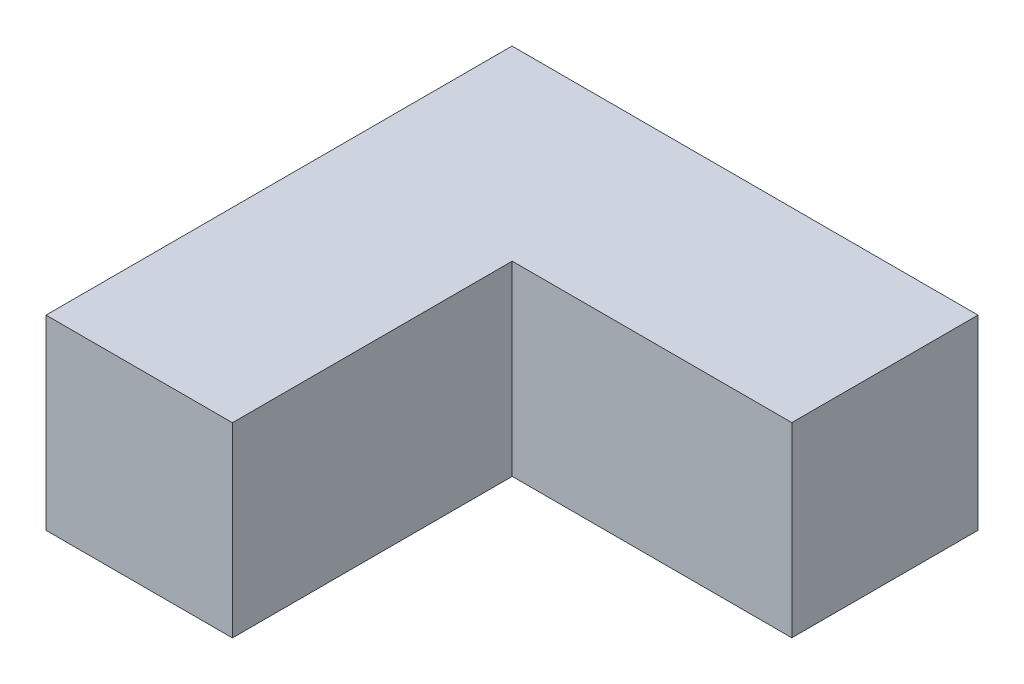
SolidWorks part; units mm, degrees
ref_plane "Plan de face" through (0, 0, 0) normal (0, 0, 1) x (1, 0, 0)
ref_plane "Plan de dessus" through (0, 0, 0) normal (0, 1, 0) x (1, 0, 0)
ref_plane "Plan de droite" through (0, 0, 0) normal (1, 0, 0) x (0, 0, -1)
sketch "Esquisse1" plane through (0, 0, 0) normal (1, 0, 0) x (0, 0, -1)
  line L1 (-2.4552, 0.3209) -> (2.5448, 0.3209)
  line L2 (-2.4552, 0.3209) -> (-2.4552, -1.6791)
  line L3 (-2.4552, -1.6791) -> (2.5448, -1.6791)
  line L4 (2.5448, 0.3209) -> (2.5448, -1.6791)
  dimension "D1" = 5
  dimension "D2" = 2
extrude "Boss.-Extru.1" add sketch "Esquisse1" along normal blind 2
sketch "Esquisse2" plane through (2, 0, 0) normal (1, 0, 0) x (0, 0, -1)
  line L0 (-2.4552, -1.6791) -> (2.5448, -1.6791) construction
  line L1 (2.5448, 0.3209) -> (0.5471, 0.3209)
  line L2 (2.5448, 0.3209) -> (2.5448, -1.6791)
  line L3 (2.5448, -1.6791) -> (0.5471, -1.6791)
  line L4 (0.5471, 0.3209) -> (0.5471, -1.6791)
extrude "Boss.-Extru.2" add sketch "Esquisse2" along normal blind 3
